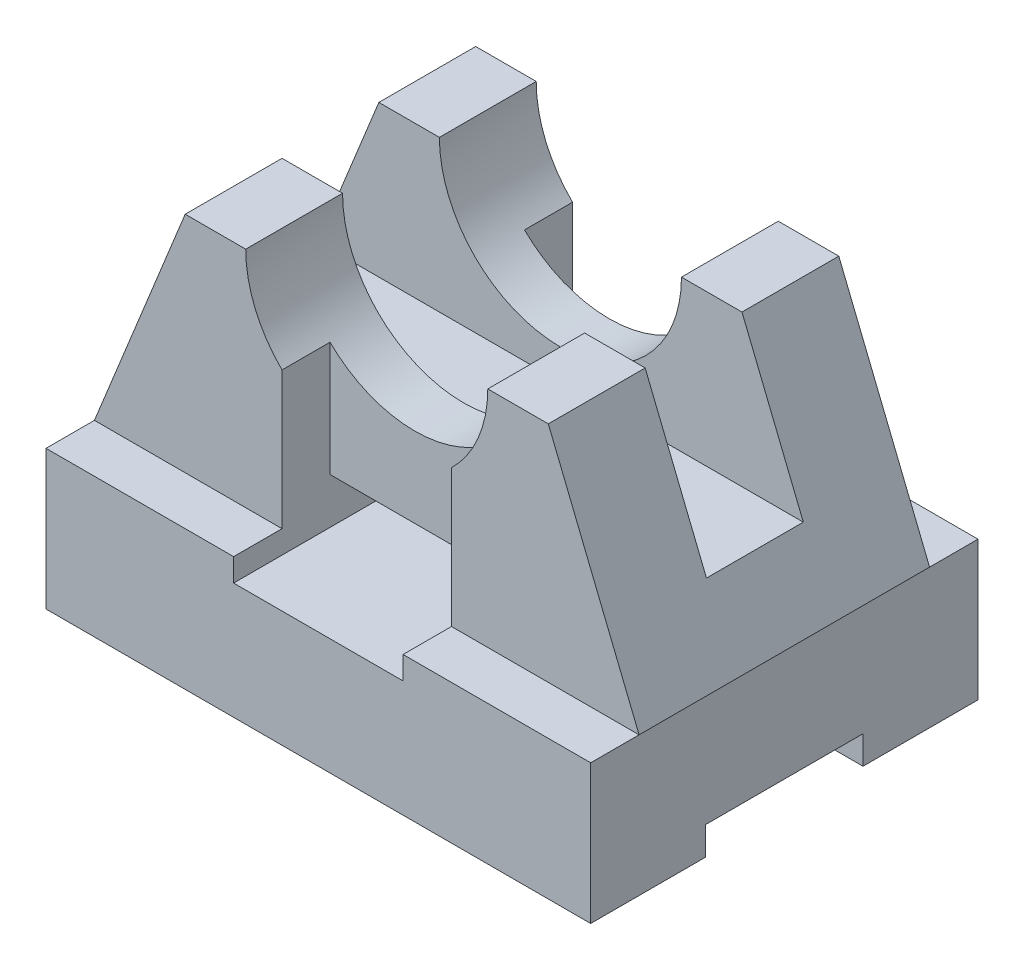
SolidWorks part; units mm, degrees
ref_plane "Front Plane" through (0, 0, 0) normal (0, 0, 1) x (1, 0, 0)
ref_plane "Top Plane" through (0, 0, 0) normal (0, 1, 0) x (1, 0, 0)
ref_plane "Right Plane" through (0, 0, 0) normal (1, 0, 0) x (0, 0, -1)
sketch "Sketch1" plane through (0, 0, 0) normal (0, 1, 0) x (1, 0, 0)
  line L1 (-45, -32) -> (45, -32)
  line L2 (-45, -32) -> (-45, 32)
  line L3 (-45, 32) -> (45, 32)
  line L4 (45, -32) -> (45, 32)
  line L5 (-45, -32) -> (45, 32) construction
  line L6 (-45, 32) -> (45, -32) construction
  point P0 (0, 0)
  dimension "D1" = 90
  dimension "D2" = 64
extrude "Boss-Extrude1" add sketch "Sketch1" along normal blind 23
sketch "Sketch3" plane through (-45, 0, 0) normal (-1, 0, 0) x (0, 0, 1)
  line L1 (-13, -4.6588) -> (13, -4.6588)
  line L2 (-13, -4.6588) -> (-13, 4.6588)
  line L3 (-13, 4.6588) -> (13, 4.6588)
  line L4 (13, -4.6588) -> (13, 4.6588)
  line L5 (-13, -4.6588) -> (13, 4.6588) construction
  line L6 (-13, 4.6588) -> (13, -4.6588) construction
  point P0 (0, 0)
  dimension "D1" = 26
extrude "Cut-Extrude1" cut sketch "Sketch3" against normal through all
sketch "Sketch4" plane through (0, 0, 32) normal (0, 0, 1) x (1, 0, 0)
  line L0 (-45, 23) -> (45, 23) construction
  line L1 (-14, 19.2147) -> (14, 19.2147)
  line L2 (-14, 19.2147) -> (-14, 26.7853)
  line L3 (-14, 26.7853) -> (14, 26.7853)
  line L4 (14, 19.2147) -> (14, 26.7853)
  line L5 (-14, 19.2147) -> (14, 26.7853) construction
  line L6 (-14, 26.7853) -> (14, 19.2147) construction
  point P0 (0, 23)
  dimension "D1" = 28
extrude "Cut-Extrude2" cut sketch "Sketch4" against normal through all
sketch "Sketch5" plane through (0, 0, 32) normal (0, 0, 1) x (1, 0, 0)
  line L2 (-30, 60) -> (30, 60)
  line L3 (-45, 23) -> (45, 23)
  line L4 (-14, 23) -> (-14, 19.2147) construction
  line L5 (-45, 23) -> (-30, 60)
  line L6 (30, 60) -> (45, 23)
  dimension "D1" = 37
  dimension "D2" = 37
  dimension "D3" = 60
  dimension "D4" = 44
extrude "Boss-Extrude2" add sketch "Sketch5" against normal through all
sketch "Sketch7" plane through (-45, 0, 0) normal (-1, 0, 0) x (0, 0, 1)
  line L0 (-32, 23) -> (-32, 60)
  line L1 (-32, 60) -> (-24, 60)
  line L3 (-24, 60) -> (-24, 23)
  line L5 (-24, 23) -> (-32, 23)
  line L6 (0, -33) -> (0, 33) construction
  line L7 (24, 23) -> (32, 23)
  line L8 (32, 60) -> (24, 60)
  line L9 (24, 60) -> (24, 23)
  line L10 (32, 23) -> (32, 60)
  dimension "D1" = 8
extrude "Cut-Extrude3" cut sketch "Sketch7" against normal through all both and the other way through all
sketch "Sketch8" plane through (-45, 0, 0) normal (-1, 0, 0) x (0, 0, 1)
  line L2 (-8, 60) -> (8, 60)
  line L3 (-8, 60) -> (-8, 35)
  line L4 (-8, 35) -> (8, 35)
  line L5 (8, 60) -> (8, 35)
  dimension "D1" = 25
  dimension "D2" = 16
extrude "Cut-Extrude4" cut sketch "Sketch8" against normal through all both and the other way through all
sketch "Sketch9" plane through (0, 0, 24) normal (0, 0, 1) x (1, 0, 0)
  line L0 (30, 60) -> (-30, 60) construction
  circle A0 centre (0, 60) radius 20
  dimension "D1" = 40
extrude "Cut-Extrude5" cut sketch "Sketch9" against normal through all both and the other way through all
sketch "Sketch11" plane through (0, 19.2147, 0) normal (0, 1, 0) x (1, 0, 0)
  line L0 (-14, -32) -> (-14, -16.0667)
  line L1 (-14, 32) -> (-14, -32) construction
  line L2 (-14, -16.0667) -> (14, -16.0667)
  line L3 (14, -16.0667) -> (14, -32)
  line L4 (14, -32) -> (-14, -32)
extrude "Cut-Extrude6" cut sketch "Sketch11" along normal through all
mirror "Mirror1" about plane through (0, 0, 0) normal (0, 0, 1) of "Cut-Extrude2", "Cut-Extrude6"
